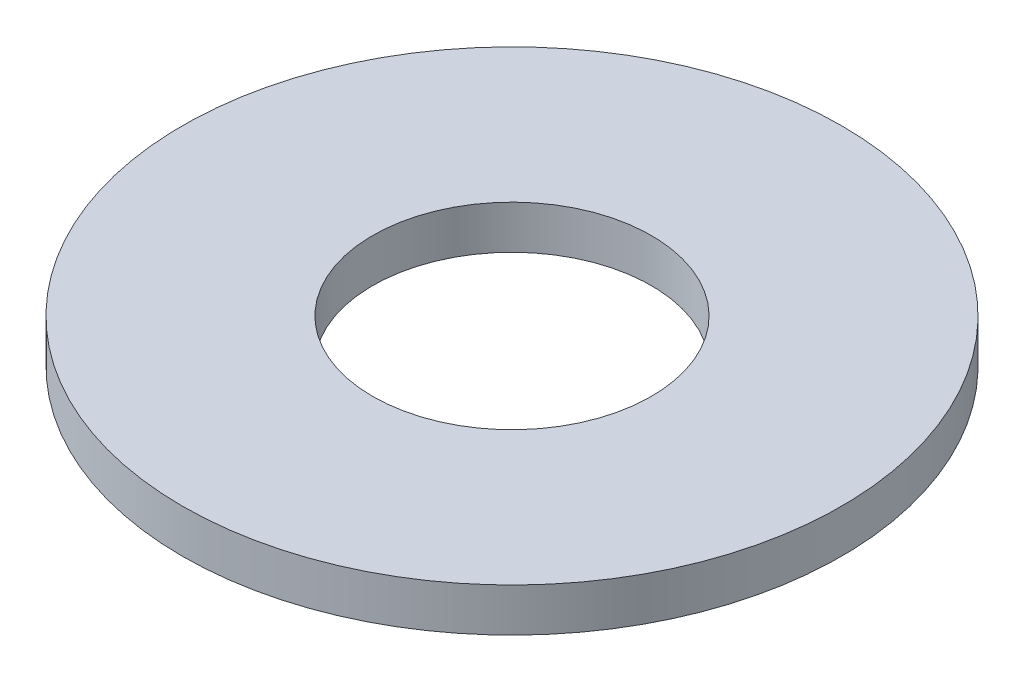
SolidWorks part; units mm, degrees
ref_plane "Front Plane" through (0, 0, 0) normal (0, 0, 1) x (1, 0, 0)
ref_plane "Top Plane" through (0, 0, 0) normal (0, 1, 0) x (1, 0, 0)
ref_plane "Right Plane" through (0, 0, 0) normal (1, 0, 0) x (0, 0, -1)
sketch "Sketch1" plane through (0, 0, 0) normal (0, 1, 0) x (1, 0, 0)
  line L0 (0, 37.95) -> (0, 16.05) construction
  circle A0 centre (0, 0) radius 37.95
  circle A1 centre (0, 0) radius 16.05
  dimension "D1" = 75.9
  dimension "D2" = 32.1
extrude "Boss-Extrude1" add sketch "Sketch1" along normal blind 5
